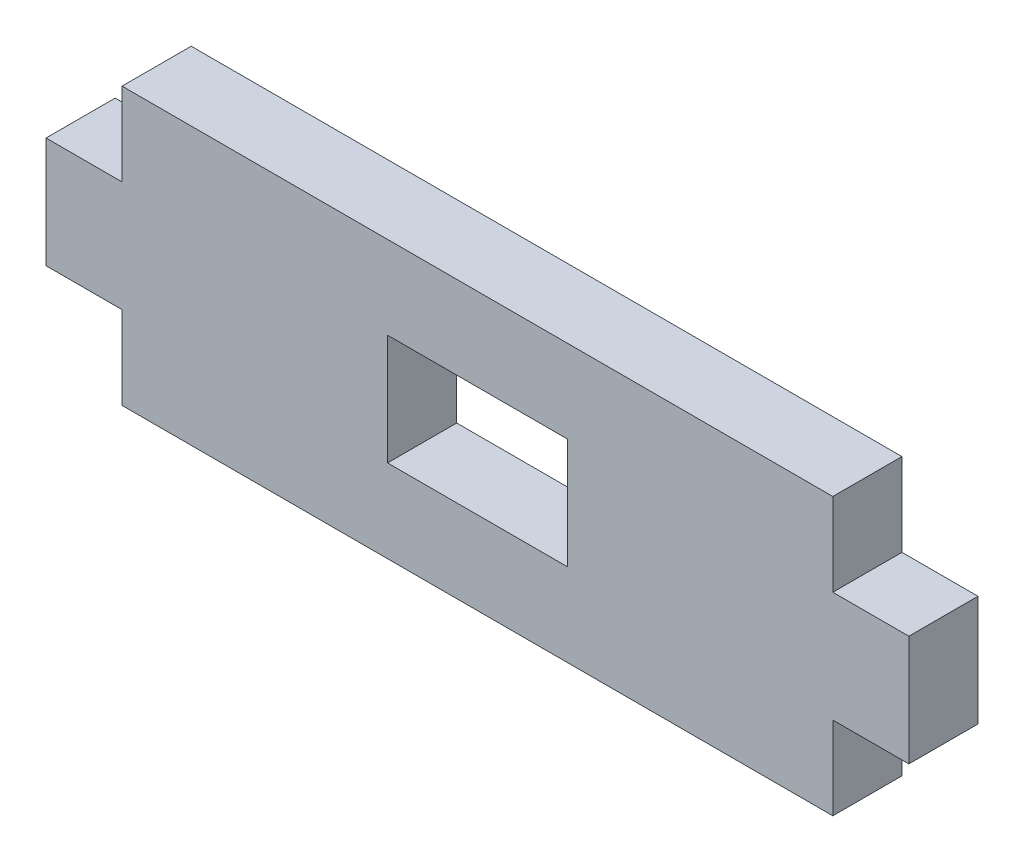
SolidWorks part; units mm, degrees
ref_plane "Front Plane" through (0, 0, 0) normal (0, 0, 1) x (1, 0, 0)
ref_plane "Top Plane" through (0, 0, 0) normal (0, 1, 0) x (1, 0, 0)
ref_plane "Right Plane" through (0, 0, 0) normal (1, 0, 0) x (0, 0, -1)
sketch "Sketch1" plane through (0, 0, 0) normal (0, 0, 1) x (1, 0, 0)
  line L0 (-25.7, 10) -> (-25.7, -10)
  line L1 (-25.7, 10) -> (25.7, 10)
  line L3 (-25.7, -10) -> (25.7, -10)
  line L5 (-25.7, 10) -> (25.7, -10) construction
  line L6 (-25.7, -10) -> (25.7, 10) construction
  line L7 (-25.7, 4) -> (-31.2, 4)
  line L20 (0, 0) -> (0, 10) construction
  line L21 (0, 10) -> (0, -10) construction
  line L35 (-25.7, 0) -> (-25.7, -4)
  line L36 (-25.7, 0) -> (-25.7, 4)
  line L40 (-31.2, 4) -> (-31.2, -4)
  line L41 (-31.2, -4) -> (-25.7, -4)
  line L42 (25.7, 10) -> (25.7, -10)
  line L43 (31.2, 4) -> (31.2, -4)
  line L44 (25.7, 4) -> (31.2, 4)
  line L45 (25.7, 0) -> (25.7, 4)
  line L46 (25.7, 0) -> (25.7, -4)
  line L47 (31.2, -4) -> (25.7, -4)
  point P0 (0, 0)
  dimension "D1" = 6
  dimension "D2" = 51.4
  dimension "D3" = 4
  dimension "D4" = 4
  dimension "D5" = 5.5
  dimension "D6" = 6
  dimension "D7" = 6
  dimension "D8" = 6
  dimension "D9" = 5.5
  dimension "D10" = 62.4
extrude "Boss-Extrude1" add sketch "Sketch1" along normal blind 5
sketch "Sketch2" plane through (0, 0, 5) normal (0, 0, 1) x (1, 0, 0)
  line L1 (-6.5, 4) -> (6.5, 4)
  line L2 (-6.5, 4) -> (-6.5, -4)
  line L3 (-6.5, -4) -> (6.5, -4)
  line L4 (6.5, 4) -> (6.5, -4)
  line L5 (-6.5, 4) -> (6.5, -4) construction
  line L6 (-6.5, -4) -> (6.5, 4) construction
  point P0 (0, 0)
  dimension "D1" = 13
  dimension "D2" = 8
extrude "Cut-Extrude1" cut sketch "Sketch2" against normal blind 5
equation "\"ภ\"=5"
